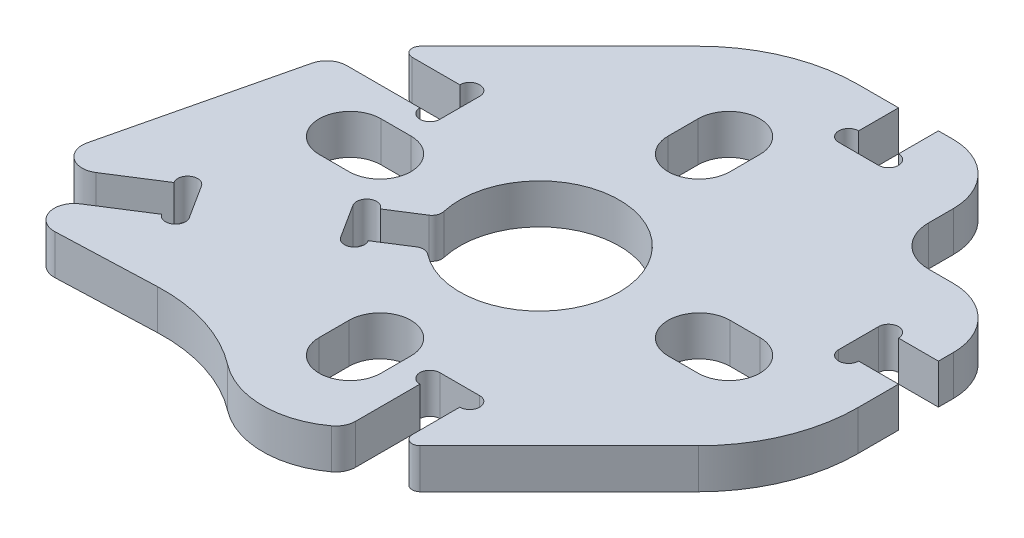
SolidWorks part; units mm, degrees
material "ABS"
ref_plane "Front Plane" through (0, 0, 0) normal (0, 0, 1) x (1, 0, 0)
ref_plane "Top Plane" through (0, 0, 0) normal (0, 1, 0) x (1, 0, 0)
ref_plane "Right Plane" through (0, 0, 0) normal (1, 0, 0) x (0, 0, -1)
sketch "Sketch2" plane through (0, 0, 0) normal (0, 1, 0) x (1, 0, 0)
  line L0 (-10.6834, 7.4533) -> (-10.6834, 5.4533)
  line L1 (-11.6834, 7.4533) -> (-14.0666, 7.4533)
  line L2 (-11.6834, 5.4533) -> (-15.3549, 5.4533)
  line L3 (-16.3274, 4.6861) -> (-18.5026, -4.4013)
  line L4 (-16.9927, -5.4774) -> (-14.6065, -3.9572)
  line L5 (-13.5319, -5.644) -> (-16.026, -7.2329)
  line L6 (-15.4513, -9.0756) -> (-10.493, -8.8902)
  line L7 (0.3166, -9.768) -> (0.3166, -6.5471)
  line L8 (0.3166, -5.5471) -> (2.3166, -5.5471)
  line L9 (2.3166, -6.5471) -> (2.3166, -8.9303)
  line L10 (2.9994, -9.2131) -> (9.9734, -2.2391)
  line L11 (12.3166, 5.4533) -> (10.3166, 5.4533)
  line L12 (9.3166, 5.4533) -> (9.3166, 7.4533)
  line L13 (10.3166, 7.4533) -> (12.3166, 7.4533)
  line L14 (12.3166, 7.4533) -> (12.3166, 8.2029)
  line L15 (9.3166, 11.2029) -> (8.0666, 11.2029)
  line L16 (6.0666, 13.2029) -> (6.0666, 14.4529)
  line L17 (3.0666, 17.4529) -> (2.3166, 17.4529)
  line L18 (2.3166, 17.4529) -> (2.3166, 15.4529)
  line L19 (0.3166, 15.4529) -> (0.3166, 17.4533)
  line L20 (0.3166, 17.4533) -> (-1.7186, 17.4533)
  line L21 (-7.3755, 15.1101) -> (-14.3495, 8.1361)
  line L22 (-13.7631, -3.4199) -> (-12.6885, -5.1067)
  line L23 (12.3166, 5.4533) -> (12.3166, 3.4177)
  line L24 (0.3166, 14.4529) -> (2.3166, 14.4529)
  line L25 (-1.1334, 11.9529) -> (-1.1334, 10.4529)
  line L26 (-4.2334, 11.9529) -> (-4.2334, 10.4529)
  line L27 (5.3166, 4.0029) -> (6.8166, 4.0029)
  line L28 (5.3166, 0.9029) -> (6.8166, 0.9029)
  line L29 (-1.1334, -5.5471) -> (-1.1334, -7.0471)
  line L30 (-4.2334, -5.5471) -> (-4.2334, -7.0471)
  line L31 (-10.6834, 0.9029) -> (-12.1834, 0.9029)
  line L32 (-10.6834, 4.0029) -> (-12.1834, 4.0029)
  line L33 (-8.2811, 0.0725) -> (-6.7989, 1.0167)
  line L34 (-7.2065, -1.6143) -> (-5.7243, -0.67)
  line L35 (-9.1245, -0.4648) -> (-8.0499, -2.1516)
  line L36 (-13.2258, -4.2633) -> (-2.6834, 2.4529) construction
  line L37 (-44.2539, 0) -> (44.2539, 0) construction
  line L38 (-2.6834, 2.4529) -> (5.3166, 2.4529) construction
  line L39 (-2.6834, 2.4529) -> (-2.6834, 10.4529) construction
  line L40 (-2.6834, 2.4529) -> (-10.6834, 2.4529) construction
  line L41 (-2.6834, 2.4529) -> (-2.6834, -5.5471) construction
  line L42 (-2.6834, 11.9529) -> (-2.6834, 10.4529) construction
  line L43 (5.3166, 2.4529) -> (6.8166, 2.4529) construction
  line L44 (-2.6834, -5.5471) -> (-2.6834, -7.0471) construction
  line L45 (-10.6834, 2.4529) -> (-12.1834, 2.4529) construction
  line L46 (-10.6834, 6.4533) -> (9.3166, 6.4533) construction
  line L47 (1.3166, 14.4529) -> (1.3166, -5.5471) construction
  arc A0 (-14.3495, 8.1361) -> (-14.0666, 7.4533) centre (-14.0666, 7.8533) ccw
  arc A1 (-10.6834, 7.4533) -> (-11.6834, 7.4533) centre (-11.1834, 7.4533) ccw
  arc A2 (-10.6834, 5.4533) -> (-11.6834, 5.4533) centre (-11.1834, 5.4533) cw
  arc A3 (-15.3549, 5.4533) -> (-16.3274, 4.6861) centre (-15.3549, 4.4533) ccw
  arc A4 (-18.5026, -4.4013) -> (-16.9927, -5.4774) centre (-17.53, -4.634) ccw
  arc A5 (-16.026, -7.2329) -> (-15.4513, -9.0756) centre (-15.4887, -8.0763) ccw
  arc A6 (-13.7631, -3.4199) -> (-14.6065, -3.9572) centre (-14.1848, -3.6886) ccw
  arc A7 (-12.6885, -5.1067) -> (-13.5319, -5.644) centre (-13.1102, -5.3754) cw
  arc A8 (-10.493, -8.8902) -> (-5.3394, -10.526) centre (-10.1941, -16.8846) cw
  arc A9 (-5.3394, -10.526) -> (-0.0912, -10.5737) centre (-2.6834, -7.0471) ccw
  arc A10 (0.3166, -9.768) -> (-0.0912, -10.5737) centre (-0.6834, -9.768) cw
  arc A11 (0.3166, -5.5471) -> (0.3166, -6.5471) centre (0.3166, -6.0471) ccw
  arc A12 (2.3166, -5.5471) -> (2.3166, -6.5471) centre (2.3166, -6.0471) cw
  arc A13 (2.3166, -8.9303) -> (2.9994, -9.2131) centre (2.7166, -8.9303) ccw
  arc A14 (9.9734, -2.2391) -> (12.3166, 3.4177) centre (4.3166, 3.4177) ccw
  arc A15 (9.3166, 11.2029) -> (12.3166, 8.2029) centre (9.3166, 8.2029) cw
  arc A16 (8.0666, 11.2029) -> (6.0666, 13.2029) centre (8.0666, 13.2029) cw
  arc A17 (6.0666, 14.4529) -> (3.0666, 17.4529) centre (3.0666, 14.4529) ccw
  arc A18 (-1.7186, 17.4533) -> (-7.3755, 15.1101) centre (-1.7186, 9.4533) ccw
  arc A19 (-4.2334, 11.9529) -> (-1.1334, 11.9529) centre (-2.6834, 11.9529) cw
  arc A20 (-4.2334, 10.4529) -> (-1.1334, 10.4529) centre (-2.6834, 10.4529) ccw
  arc A21 (-10.6834, 4.0029) -> (-10.6834, 0.9029) centre (-10.6834, 2.4529) cw
  arc A22 (-12.1834, 4.0029) -> (-12.1834, 0.9029) centre (-12.1834, 2.4529) ccw
  arc A23 (2.3166, 14.4529) -> (2.3166, 15.4529) centre (2.3166, 14.9529) ccw
  arc A24 (0.3166, 14.4529) -> (0.3166, 15.4529) centre (0.3166, 14.9529) cw
  arc A25 (9.3166, 7.4533) -> (10.3166, 7.4533) centre (9.8166, 7.4533) cw
  arc A26 (9.3166, 5.4533) -> (10.3166, 5.4533) centre (9.8166, 5.4533) ccw
  arc A27 (-9.1245, -0.4648) -> (-8.2811, 0.0725) centre (-8.7028, -0.1961) cw
  arc A28 (-8.0499, -2.1516) -> (-7.2065, -1.6143) centre (-7.6282, -1.8829) ccw
  arc A29 (-5.7243, -0.67) -> (-5.1476, -0.6979) centre (-5.4557, -1.0917) cw
  arc A30 (-5.1476, -0.6979) -> (-6.5804, 1.5512) centre (-2.6834, 2.4529) ccw
  arc A31 (-6.7989, 1.0167) -> (-6.5804, 1.5512) centre (-7.0676, 1.4384) ccw
  arc A32 (5.3166, 4.0029) -> (5.3166, 0.9029) centre (5.3166, 2.4529) ccw
  arc A33 (6.8166, 4.0029) -> (6.8166, 0.9029) centre (6.8166, 2.4529) cw
  arc A34 (-1.1334, -5.5471) -> (-4.2334, -5.5471) centre (-2.6834, -5.5471) ccw
  arc A35 (-4.2334, -7.0471) -> (-1.1334, -7.0471) centre (-2.6834, -7.0471) ccw
  point P108 (-8.5872, -1.3082)
  point P115 (-0.6834, 6.4533)
  point P116 (1.3166, 4.4529)
  point P117 (1.3166, 14.4529)
  point P118 (9.3166, 6.4533)
  dimension "D6" = 1.55
  dimension "D7" = 0.5
  dimension "D9" = 4
  dimension "D1" = 4
  dimension "D2" = 4.0004
  dimension "D3" = 32.5
  dimension "D4" = 8
  dimension "D5" = 1.5
  dimension "D8" = 2
  dimension "D10" = 2
  dimension "D11" = 5.5
  dimension "D12" = 7
  dimension "D13" = 2
  dimension "D14" = 20
extrude "Boss-Extrude1" add sketch "Sketch2" along normal blind 2
